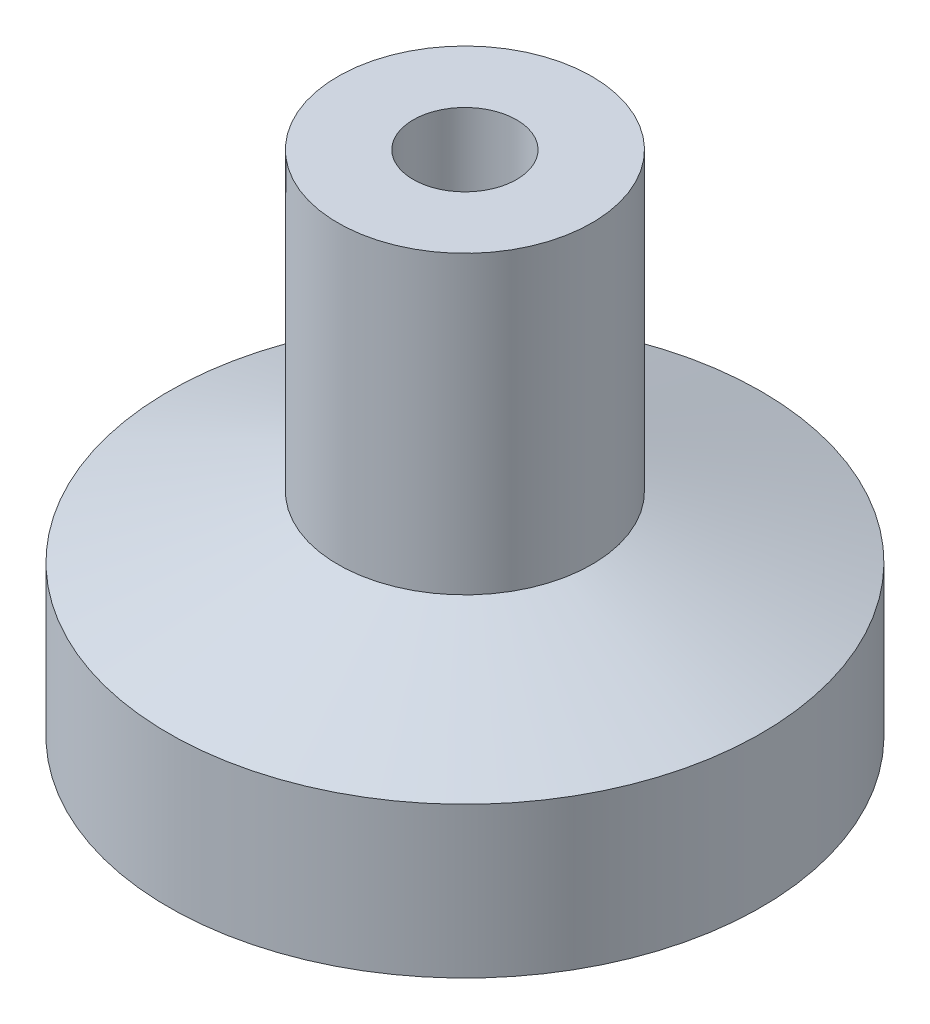
SolidWorks part; units mm, degrees
ref_plane "Front Plane" through (0, 0, 0) normal (0, 0, 1) x (1, 0, 0)
ref_plane "Top Plane" through (0, 0, 0) normal (0, 1, 0) x (1, 0, 0)
ref_plane "Right Plane" through (0, 0, 0) normal (1, 0, 0) x (0, 0, -1)
sketch "Sketch1" plane through (0, 0, 0) normal (0, 0, 1) x (1, 0, 0)
  line L0 (0, 0) -> (0, 27) construction
  line L1 (-2.75, 0) -> (-15.75, 0)
  line L2 (-2.75, 0) -> (-2.75, 27)
  line L3 (-2.75, 27) -> (-6.75, 27)
  line L5 (-15.75, 0) -> (-15.75, 8)
  line L7 (-6.75, 11.2757) -> (-6.75, 27)
  line L8 (-15.75, 8) -> (-6.75, 11.2757)
  dimension "D2" = 4
  dimension "D3" = 2.75
  dimension "D1" = 27
  dimension "D4" = 8
  dimension "D5" = 13
  dimension "D6" = 20
revolve "Revolve1" add sketch "Sketch1" angle 360 about L0
equation "\"D3@Sketch1\"=5.5/2"
